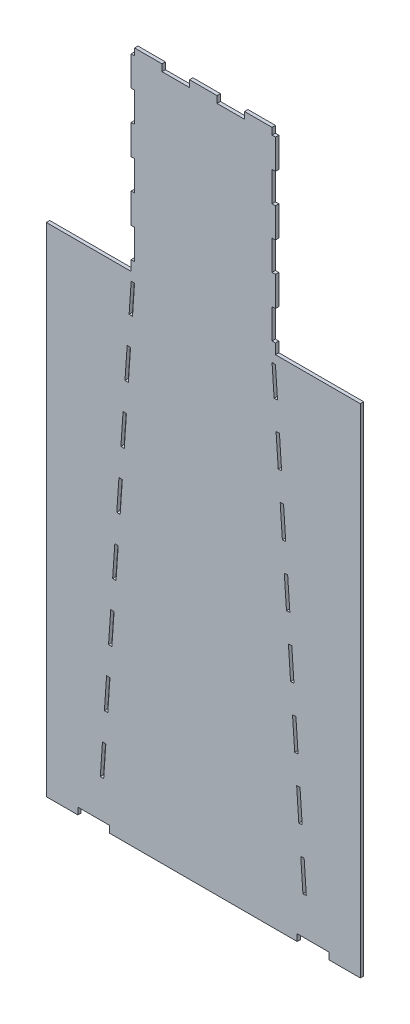
SolidWorks part; units mm, degrees
material "A-Glass Fiber"
ref_plane "Front Plane" through (0, 0, 0) normal (0, 0, 1) x (1, 0, 0)
ref_plane "Top Plane" through (0, 0, 0) normal (0, 1, 0) x (1, 0, 0)
ref_plane "Right Plane" through (0, 0, 0) normal (1, 0, 0) x (0, 0, -1)
sketch "Sketch1" plane through (0, 0, 0) normal (0, 0, 1) x (1, 0, 0)
  line L0 (-215.8818, 2072.64) -> (-215.8818, 1463.04) construction
  line L1 (308.2661, 132.944) -> (301.7555, 226.6808) construction
  line L2 (-292.1, 0) -> (292.1, 0) construction
  line L3 (-215.8818, 2072.64) -> (215.8818, 2072.64) construction
  line L4 (301.7555, 226.6808) -> (291.6378, 225.9781) construction
  line L5 (-205.7153, 2072.64) -> (-123.444, 2072.64)
  line L6 (-123.444, 2052.32) -> (-123.444, 2072.64)
  line L7 (-123.444, 2052.32) -> (-123.444, 2072.64)
  line L8 (-41.1356, 2072.64) -> (-41.1356, 2052.32)
  line L9 (-41.1356, 2072.64) -> (41.1356, 2072.64)
  line L10 (0, 2072.64) -> (0, 0) construction
  line L11 (291.6378, 225.9781) -> (298.1484, 132.2412) construction
  line L12 (-280.9748, 20.32) -> (280.9748, 20.32)
  line L13 (298.1484, 132.2412) -> (308.2661, 132.944) construction
  line L14 (289.4357, 404.0535) -> (279.318, 403.3508) construction
  line L15 (279.318, 403.3508) -> (285.8305, 309.5874) construction
  line L16 (285.8305, 309.5874) -> (295.9482, 310.2901) construction
  line L17 (-205.7153, 2072.64) -> (-123.444, 2072.64) construction
  line L18 (-205.7153, 2072.64) -> (-205.7153, 1963.42)
  line L19 (-205.7153, 1963.42) -> (-215.8818, 1963.42)
  line L20 (-215.8818, 2052.32) -> (-215.8818, 1963.42)
  line L21 (-205.7153, 1963.42) -> (-215.8818, 1963.42)
  line L23 (-205.7153, 1874.52) -> (-215.8818, 1874.52)
  line L26 (295.9482, 310.2901) -> (289.4357, 404.0535) construction
  line L28 (205.7153, 1696.72) -> (215.8753, 1696.72)
  line L29 (215.8753, 1696.72) -> (215.8753, 1607.82)
  line L30 (205.7153, 1696.72) -> (215.8753, 1696.72)
  line L31 (205.7153, 1607.82) -> (215.8753, 1607.82)
  line L32 (283.6303, 487.6362) -> (277.1159, 581.4262) construction
  line L33 (205.7153, 1607.82) -> (215.8753, 1607.82)
  line L34 (-205.7153, 1518.92) -> (215.8818, 1518.92)
  line L35 (205.7153, 1785.62) -> (215.8818, 1785.62)
  line L36 (-205.7153, 1518.92) -> (215.8818, 1518.92)
  line L37 (-215.8818, 1463.04) -> (-205.7153, 1463.04)
  line L38 (277.1159, 581.4262) -> (266.9983, 580.7234) construction
  line L39 (-215.8818, 1463.04) -> (-205.7153, 1463.04) construction
  line L40 (-205.7153, 1463.04) -> (-205.7153, 2072.64)
  line L41 (266.9983, 580.7234) -> (273.5126, 486.9335) construction
  line L42 (273.5126, 486.9335) -> (283.6303, 487.6362) construction
  line L43 (264.7962, 758.7989) -> (254.6785, 758.0961) construction
  line L44 (215.8818, 1463.04) -> (205.7153, 1463.04) construction
  line L45 (254.6785, 758.0961) -> (261.1947, 664.2796) construction
  line L46 (261.1947, 664.2796) -> (271.3124, 664.9824) construction
  line L47 (271.3124, 664.9824) -> (264.7962, 758.7989) construction
  line L48 (252.4764, 936.1715) -> (242.3588, 935.4688) construction
  line L50 (242.3588, 935.4688) -> (248.8768, 841.6258) construction
  line L52 (248.8768, 841.6258) -> (258.9945, 842.3285) construction
  line L53 (258.9945, 842.3285) -> (252.4764, 936.1715) construction
  line L54 (240.1567, 1113.5442) -> (230.039, 1112.8414) construction
  line L55 (230.039, 1112.8414) -> (236.5589, 1018.9719) construction
  line L56 (236.5589, 1018.9719) -> (246.6766, 1019.6747) construction
  line L57 (246.6766, 1019.6747) -> (240.1567, 1113.5442) construction
  line L58 (227.8369, 1290.9169) -> (217.7192, 1290.2141) construction
  line L59 (217.7192, 1290.2141) -> (224.241, 1196.3181) construction
  line L60 (224.241, 1196.3181) -> (234.3587, 1197.0208) construction
  line L61 (234.3587, 1197.0208) -> (227.8369, 1290.9169) construction
  line L62 (205.7153, 1463.04) -> (211.9231, 1373.6642) construction
  line L63 (211.9231, 1373.6642) -> (222.0407, 1374.3669) construction
  line L64 (222.0407, 1374.3669) -> (215.8818, 1463.04) construction
  line L65 (215.8818, 1463.04) -> (205.7153, 1463.04) construction
  line L66 (-211.9231, 1373.6642) -> (-205.7153, 1463.04) construction
  line L67 (-280.9748, 20.32) -> (-291.0414, 20.32)
  line L68 (-205.7153, 1463.04) -> (-215.8818, 1463.04) construction
  line L69 (-215.8818, 1463.04) -> (-222.0407, 1374.3669) construction
  line L70 (-280.9748, 20.32) -> (-280.9748, 0)
  line L71 (-222.0407, 1374.3669) -> (-211.9231, 1373.6642) construction
  line L72 (-217.7192, 1290.2141) -> (-227.8369, 1290.9169) construction
  line L73 (-227.8369, 1290.9169) -> (-234.3587, 1197.0208) construction
  line L74 (-234.3587, 1197.0208) -> (-224.241, 1196.3181) construction
  line L75 (-224.241, 1196.3181) -> (-217.7192, 1290.2141) construction
  line L76 (-230.039, 1112.8414) -> (-240.1567, 1113.5442) construction
  line L77 (-240.1567, 1113.5442) -> (-246.6766, 1019.6747) construction
  line L78 (-168.402, 20.32) -> (-168.402, 0)
  line L79 (-246.6766, 1019.6747) -> (-236.5589, 1018.9719) construction
  line L80 (-236.5589, 1018.9719) -> (-230.039, 1112.8414) construction
  line L81 (-242.3588, 935.4688) -> (-252.4764, 936.1715) construction
  line L82 (205.7153, 2072.64) -> (123.444, 2072.64) construction
  line L83 (-168.402, 20.32) -> (-168.402, 0)
  line L86 (-205.7153, 2052.32) -> (-215.8818, 2052.32)
  line L87 (292.1, 0) -> (-292.1, 0)
  line L88 (-280.9748, 0) -> (-168.402, 0)
  line L89 (-252.4764, 936.1715) -> (-258.9945, 842.3285) construction
  line L90 (215.8818, 2072.64) -> (215.8818, 1463.04) construction
  line L91 (-215.8818, 2052.32) -> (-205.7153, 2052.32)
  line L92 (215.8818, 2052.32) -> (205.7153, 2052.32)
  line L93 (280.9748, 0) -> (168.402, 0)
  line L94 (205.7153, 2052.32) -> (-215.8818, 2052.32)
  line L97 (168.402, 20.32) -> (168.402, 0)
  line L98 (-258.9945, 842.3285) -> (-248.8768, 841.6258) construction
  line L99 (-248.8768, 841.6258) -> (-242.3588, 935.4688) construction
  line L100 (168.402, 20.32) -> (168.402, 0)
  line L101 (-254.6785, 758.0961) -> (-264.7962, 758.7989) construction
  line L102 (-264.7962, 758.7989) -> (-271.3124, 664.9824) construction
  line L104 (-271.3124, 664.9824) -> (-261.1947, 664.2796) construction
  line L105 (-261.1947, 664.2796) -> (-254.6785, 758.0961) construction
  line L106 (-277.1159, 581.4262) -> (-283.6303, 487.6362) construction
  line L107 (-283.6303, 487.6362) -> (-273.5126, 486.9335) construction
  line L108 (280.9748, 20.32) -> (280.9748, 0)
  line L109 (-273.5126, 486.9335) -> (-266.9983, 580.7234) construction
  line L110 (280.9748, 20.32) -> (291.0414, 20.32)
  line L111 (-266.9983, 580.7234) -> (-277.1159, 581.4262) construction
  line L112 (-279.318, 403.3508) -> (-289.4357, 404.0535) construction
  line L113 (-289.4357, 404.0535) -> (-295.9482, 310.2901) construction
  line L114 (-295.9482, 310.2901) -> (-285.8305, 309.5874) construction
  line L116 (-285.8305, 309.5874) -> (-279.318, 403.3508) construction
  line L117 (-301.7555, 226.6808) -> (-308.2661, 132.944) construction
  line L120 (-308.2661, 132.944) -> (-298.1484, 132.2412) construction
  line L121 (-298.1484, 132.2412) -> (-291.6378, 225.9781) construction
  line L124 (-291.6378, 225.9781) -> (-301.7555, 226.6808) construction
  line L125 (308.2661, 132.944) -> (301.7555, 226.6808)
  line L127 (301.7555, 226.6808) -> (291.6378, 225.9781)
  line L128 (205.7153, 1463.04) -> (205.7153, 2072.64)
  line L129 (215.8818, 1463.04) -> (205.7153, 1463.04)
  line L130 (205.7153, 1518.92) -> (-215.8818, 1518.92)
  line L131 (-205.7153, 1518.92) -> (-215.8818, 1518.92)
  line L132 (205.7153, 1518.92) -> (-215.8818, 1518.92)
  line L133 (-205.7153, 1607.82) -> (-215.8753, 1607.82)
  line L134 (291.6378, 225.9781) -> (298.1484, 132.2412)
  line L135 (-205.7153, 1607.82) -> (-215.8753, 1607.82)
  line L136 (-205.7153, 1696.72) -> (-215.8753, 1696.72)
  line L137 (-215.8753, 1696.72) -> (-215.8753, 1607.82)
  line L138 (-205.7153, 1696.72) -> (-215.8753, 1696.72)
  line L143 (-215.8818, 1518.92) -> (-215.8818, 1463.04)
  line L145 (205.7153, 1963.42) -> (215.8818, 1963.42)
  line L146 (215.8818, 2052.32) -> (215.8818, 1963.42)
  line L147 (205.7153, 1963.42) -> (215.8818, 1963.42)
  line L148 (205.7153, 2072.64) -> (205.7153, 1963.42)
  line L149 (41.1356, 2072.64) -> (41.1356, 2052.32)
  line L150 (123.444, 2052.32) -> (123.444, 2072.64)
  line L151 (123.444, 2052.32) -> (123.444, 2072.64)
  line L152 (205.7153, 2072.64) -> (123.444, 2072.64)
  line L153 (298.1484, 132.2412) -> (308.2661, 132.944)
  line L154 (205.7153, 1518.92) -> (215.8818, 1518.92)
  line L155 (215.8818, 1518.92) -> (215.8818, 1463.04)
  line L156 (-205.7153, 1785.62) -> (-215.8818, 1785.62)
  line L165 (-215.8818, 1874.52) -> (-215.8818, 1785.62)
  line L166 (215.8818, 1874.52) -> (215.8818, 1785.62)
  line L167 (205.7153, 1874.52) -> (215.8818, 1874.52)
  line L168 (215.8818, 1488.44) -> (469.8818, 1488.44)
  line L169 (-55.8292, 20.32) -> (55.8292, 20.32)
  line L170 (-55.8292, 20.32) -> (-55.8292, 0)
  line L171 (-55.8292, 0) -> (55.8292, 0)
  line L172 (55.8292, 20.32) -> (55.8292, 0)
  line L173 (469.8818, 1488.44) -> (469.8818, 20.32)
  line L174 (469.8818, 20.32) -> (291.0414, 20.32)
  line L175 (-215.8818, 1488.44) -> (-469.8818, 1488.44)
  line L176 (-469.8818, 1488.44) -> (-469.8818, 20.32)
  line L177 (-291.0414, 20.32) -> (-469.8818, 20.32)
  line L178 (289.4357, 404.0535) -> (279.318, 403.3508)
  line L179 (279.318, 403.3508) -> (285.8305, 309.5874)
  line L180 (-375.4283, 0) -> (-280.9748, 0) construction
  line L181 (-469.8818, 20.32) -> (-375.4283, 20.32)
  line L182 (-469.8818, 20.32) -> (-469.8818, 0)
  line L183 (-469.8818, 0) -> (-375.4283, 0)
  line L184 (-375.4283, 20.32) -> (-375.4283, 0)
  line L185 (280.9748, 0) -> (375.4283, 0) construction
  line L186 (-375.4283, 0) -> (-280.9748, 0)
  line L187 (-375.4283, 0) -> (-375.4283, 20.32)
  line L188 (-375.4283, 20.32) -> (-280.9748, 20.32)
  line L189 (-280.9748, 0) -> (-280.9748, 20.32)
  line L190 (469.8818, 20.32) -> (375.4283, 20.32)
  line L191 (469.8818, 20.32) -> (469.8818, 0)
  line L192 (469.8818, 0) -> (375.4283, 0)
  line L193 (375.4283, 20.32) -> (375.4283, 0)
  line L194 (285.8305, 309.5874) -> (295.9482, 310.2901)
  line L195 (375.4283, 0) -> (280.9748, 0)
  line L196 (375.4283, 0) -> (375.4283, 20.32)
  line L197 (375.4283, 20.32) -> (280.9748, 20.32)
  line L198 (280.9748, 0) -> (280.9748, 20.32)
  line L199 (295.9482, 310.2901) -> (289.4357, 404.0535)
  line L200 (283.6303, 487.6362) -> (277.1159, 581.4262)
  line L201 (277.1159, 581.4262) -> (266.9983, 580.7234)
  line L202 (266.9983, 580.7234) -> (273.5126, 486.9335)
  line L203 (273.5126, 486.9335) -> (283.6303, 487.6362)
  line L204 (264.7962, 758.7989) -> (254.6785, 758.0961)
  line L205 (254.6785, 758.0961) -> (261.1947, 664.2796)
  line L206 (261.1947, 664.2796) -> (271.3124, 664.9824)
  line L207 (271.3124, 664.9824) -> (264.7962, 758.7989)
  line L208 (252.4764, 936.1715) -> (242.3588, 935.4688)
  line L209 (242.3588, 935.4688) -> (248.8768, 841.6258)
  line L210 (248.8768, 841.6258) -> (258.9945, 842.3285)
  line L211 (258.9945, 842.3285) -> (252.4764, 936.1715)
  line L212 (240.1567, 1113.5442) -> (230.039, 1112.8414)
  line L213 (230.039, 1112.8414) -> (236.5589, 1018.9719)
  line L214 (236.5589, 1018.9719) -> (246.6766, 1019.6747)
  line L215 (246.6766, 1019.6747) -> (240.1567, 1113.5442)
  line L216 (227.8369, 1290.9169) -> (217.7192, 1290.2141)
  line L217 (217.7192, 1290.2141) -> (224.241, 1196.3181)
  line L218 (224.241, 1196.3181) -> (234.3587, 1197.0208)
  line L219 (234.3587, 1197.0208) -> (227.8369, 1290.9169)
  line L220 (205.7153, 1463.04) -> (211.9231, 1373.6642)
  line L221 (211.9231, 1373.6642) -> (222.0407, 1374.3669)
  line L222 (222.0407, 1374.3669) -> (215.8818, 1463.04)
  line L223 (215.8818, 1463.04) -> (205.7153, 1463.04)
  line L224 (-211.9231, 1373.6642) -> (-205.7153, 1463.04)
  line L225 (-205.7153, 1463.04) -> (-215.8818, 1463.04)
  line L226 (-215.8818, 1463.04) -> (-222.0407, 1374.3669)
  line L227 (-222.0407, 1374.3669) -> (-211.9231, 1373.6642)
  line L228 (-217.7192, 1290.2141) -> (-227.8369, 1290.9169)
  line L229 (-227.8369, 1290.9169) -> (-234.3587, 1197.0208)
  line L230 (-234.3587, 1197.0208) -> (-224.241, 1196.3181)
  line L231 (-224.241, 1196.3181) -> (-217.7192, 1290.2141)
  line L232 (-230.039, 1112.8414) -> (-240.1567, 1113.5442)
  line L233 (-240.1567, 1113.5442) -> (-246.6766, 1019.6747)
  line L234 (-246.6766, 1019.6747) -> (-236.5589, 1018.9719)
  line L235 (-236.5589, 1018.9719) -> (-230.039, 1112.8414)
  line L236 (-242.3588, 935.4688) -> (-252.4764, 936.1715)
  line L237 (-252.4764, 936.1715) -> (-258.9945, 842.3285)
  line L238 (-258.9945, 842.3285) -> (-248.8768, 841.6258)
  line L239 (-248.8768, 841.6258) -> (-242.3588, 935.4688)
  line L240 (-254.6785, 758.0961) -> (-264.7962, 758.7989)
  line L241 (-264.7962, 758.7989) -> (-271.3124, 664.9824)
  line L242 (-271.3124, 664.9824) -> (-261.1947, 664.2796)
  line L243 (-261.1947, 664.2796) -> (-254.6785, 758.0961)
  line L244 (-277.1159, 581.4262) -> (-283.6303, 487.6362)
  line L245 (-283.6303, 487.6362) -> (-273.5126, 486.9335)
  line L246 (-273.5126, 486.9335) -> (-266.9983, 580.7234)
  line L247 (-266.9983, 580.7234) -> (-277.1159, 581.4262)
  line L248 (-279.318, 403.3508) -> (-289.4357, 404.0535)
  line L249 (-289.4357, 404.0535) -> (-295.9482, 310.2901)
  line L250 (-295.9482, 310.2901) -> (-285.8305, 309.5874)
  line L251 (-285.8305, 309.5874) -> (-279.318, 403.3508)
  line L252 (-301.7555, 226.6808) -> (-308.2661, 132.944)
  line L253 (-308.2661, 132.944) -> (-298.1484, 132.2412)
  line L254 (-298.1484, 132.2412) -> (-291.6378, 225.9781)
  line L255 (-291.6378, 225.9781) -> (-301.7555, 226.6808)
  line L258 (469.8818, 1488.44) -> (469.8818, 0)
  line L261 (-469.8818, 1488.44) -> (-533.3818, 1488.44)
  line L262 (-469.8818, 1488.44) -> (-469.8818, 0)
  point P130 (-210.7985, 1463.04)
  point P141 (0, 20.32)
  dimension "D2" = 112.5728
  dimension "D3" = 609.6
  dimension "D4" = 2072.64
  dimension "D5" = 20.32
  dimension "D6" = 88.9
  dimension "D7" = 20.32
  dimension "D8" = 336.804
  dimension "D9" = 41.1356
  dimension "D10" = 10.1665
  dimension "D11" = 205.7153
  dimension "D12" = 10.16
  dimension "D13" = 10.16
  dimension "D14" = 88.9
  dimension "D15" = 88.9
  dimension "D16" = 88.9
  dimension "D17" = 112.5728
  dimension "D18" = 88.9
  dimension "D19" = 112.5728
  dimension "D20" = 88.9
  dimension "D21" = 20.32
  dimension "D22" = 254
  dimension "D23" = 254
  dimension "D24" = 25.4
  dimension "D25" = 25.4
extrude "Boss-Extrude1" add sketch "Sketch1" along normal blind 10.16
sketch "Sketch5" plane through (0, 0, 10.16) normal (0, 0, 1) x (1, 0, 0)
  line L1 (-533.3818, 0) -> (-469.8818, 0)
  line L2 (-533.3818, 0) -> (-533.3818, 20.32)
  line L3 (-533.3818, 20.32) -> (-469.8818, 20.32)
  line L4 (-469.8818, 0) -> (-469.8818, 20.32)
  line L5 (533.3818, 0) -> (469.8818, 0)
  line L6 (533.3818, 0) -> (533.3818, 20.32)
  line L7 (533.3818, 20.32) -> (469.8818, 20.32)
  line L8 (469.8818, 0) -> (469.8818, 20.32)
extrude "Cut-Extrude1" cut sketch "Sketch5" against normal through all
